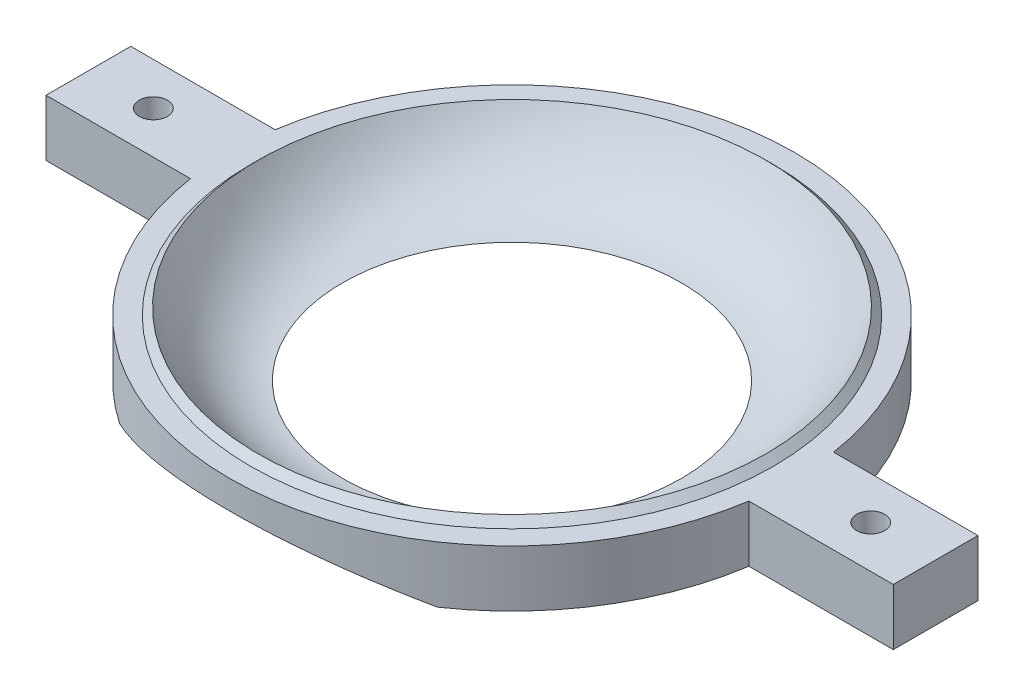
SolidWorks part; units mm, degrees
ref_plane "Front Plane" through (0, 0, 0) normal (0, 0, 1) x (1, 0, 0)
ref_plane "Top Plane" through (0, 0, 0) normal (0, 1, 0) x (1, 0, 0)
ref_plane "Right Plane" through (0, 0, 0) normal (1, 0, 0) x (0, 0, -1)
sketch "Sketch1" plane through (0, 0, 0) normal (0, 1, 0) x (1, 0, 0)
  line L0 (0, -1000) -> (0, 49000) construction
  line L1 (-15, -1.5) -> (15, -1.5)
  line L2 (-15, -1.5) -> (-15, 1.5)
  line L3 (-15, 1.5) -> (15, 1.5)
  line L4 (15, -1.5) -> (15, 1.5)
  circle A0 centre (0, 0) radius 10
  circle A1 centre (0, 0) radius 9
  circle A2 centre (-12.7, 0) radius 0.5
  circle A4 centre (12.7, 0) radius 0.5
  point P4 (0, 1.5)
  point P6 (-15, 0)
  dimension "D3" = 20
  dimension "D4" = 1
  dimension "D5" = 1
  dimension "D6" = 12.7
  dimension "D1" = 30
  dimension "D2" = 3
extrude "Boss-Extrude1" add sketch "Sketch1" along normal mid plane 2 contours A0 L3 L2 L1 A2 | A1 L3 A0 L1 | A0 L0 A1 L1 | A1 L0 A0 L3 | L0 A0 L1 A1 | L0 A1 L3 A0 | A0 L1 L4 L3 A4 | A1 L1 A0 L3
sketch "Sketch5" plane through (0, 0, 0) normal (0, 0, 1) x (1, 0, 0)
  line L0 (0, -1000) -> (0, 49000) construction
  line L1 (-9.2568, 1) -> (-9, 1.2568)
  line L3 (-9.2568, 1) -> (-9.2568, -1)
  line L4 (-9.2568, -1) -> (-8, -1)
  line L6 (-6, -1) -> (-9.2568, -1)
  line L7 (-9.2568, 1) -> (-9.2568, -1)
  line L8 (-6, -1) -> (-8, -1)
  spline S0 degree 2 poles (-9, 1.2568) (-7.8451, -0.8984) (-5.9301, -1.0046) knots 0 0 0 1 1 1
  point P7 (-9.2568, 0)
  dimension "D6" = 4
  dimension "D1" = 2
  dimension "D2" = 9
  dimension "D3" = 135
  dimension "D4" = 6
  dimension "D5" = 0.3632
  dimension "D7" = 3.3267
revolve "Revolve1" add sketch "Sketch5" angle 360 about L0
sketch "Sketch6" plane through (0, 0, 0) normal (1, 0, 0) x (0, 0, -1)
  line L0 (10, 0) -> (10, -1)
  line L1 (10, -1) -> (10, 1) construction
  line L2 (10, -1) -> (8.2679, -1)
  line L3 (1.5, -1) -> (10, -1) construction
  line L4 (8.2679, -1) -> (10, 0)
  line L5 (0, -1000) -> (0, 49000) construction
  line L6 (-10, 0) -> (-10, -1)
  line L7 (-10, -1) -> (-8.2679, -1)
  line L8 (-8.2679, -1) -> (-10, 0)
  dimension "D1" = 60
extrude "Cut-Extrude1" cut sketch "Sketch6" along normal up to surface (30 mm away) from surface at -15 up to face at (15, 0, 0) starting at face at (-15, 0, 0)
